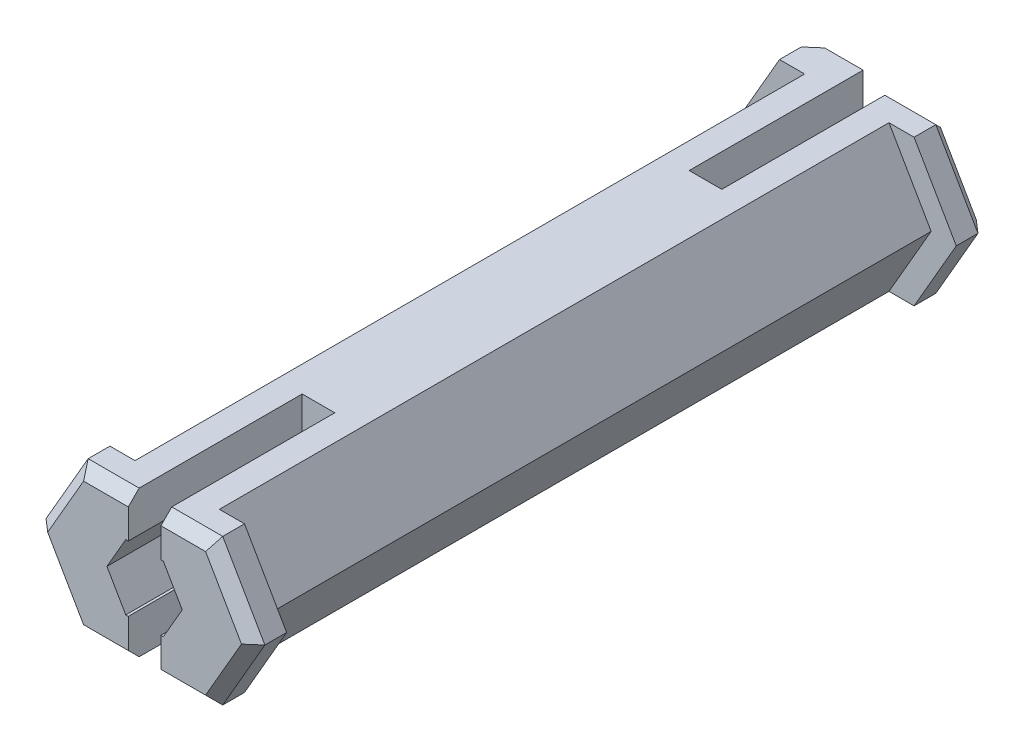
SolidWorks part; units mm, degrees
ref_plane "Plan de face" through (0, 0, 0) normal (1, 0, 0) x (0, 1, 0)
ref_plane "Plan de dessus" through (0, 0, 0) normal (0, 0, 1) x (0, 1, 0)
ref_plane "Plan de droite" through (0, 0, 0) normal (0, 1, 0) x (-1, 0, 0)
sketch "Esquisse1" plane through (0, 0, 0) normal (0, 0, 1) x (0, 1, 0)
  line L1 (0, 3.8798) -> (-3.36, 1.9399)
  line L2 (-3.36, 1.9399) -> (-3.36, -1.9399)
  line L3 (-3.36, -1.9399) -> (0, -3.8798)
  line L4 (0, -3.8798) -> (3.36, -1.9399)
  line L5 (3.36, -1.9399) -> (3.36, 1.9399)
  line L6 (3.36, 1.9399) -> (0, 3.8798)
  circle A0 centre (0, 0) radius 3.36 construction
  dimension "D1" = 6.72
extrude "Boss.-Extru.1" add sketch "Esquisse1" along normal mid plane 30.8
sketch "Esquisse2" plane through (0, 0, 15.4) normal (0, 0, 1) x (1, 0, 0)
  line L6 (-3.0946, 3.36) -> (3.0946, 3.36)
  line L7 (1.9399, 3.36) -> (-1.9399, 3.36) construction
  line L8 (-3.0946, -3.36) -> (3.0946, -3.36)
  line L9 (-1.9399, -3.36) -> (1.9399, -3.36) construction
  line L12 (-2.5172, 4.36) -> (-5.0345, 0)
  line L13 (-5.0345, 0) -> (-2.5172, -4.36)
  line L14 (-2.5172, -4.36) -> (2.5172, -4.36)
  line L15 (2.5172, -4.36) -> (5.0345, 0)
  line L16 (5.0345, 0) -> (2.5172, 4.36)
  line L17 (2.5172, 4.36) -> (-2.5172, 4.36)
  line L18 (-2.5172, 4.36) -> (-5.0345, 0)
  line L19 (-5.0345, 0) -> (-2.5172, -4.36)
  line L20 (-2.5172, -4.36) -> (2.5172, -4.36)
  line L21 (2.5172, -4.36) -> (5.0345, 0)
  line L22 (5.0345, 0) -> (2.5172, 4.36)
  line L23 (2.5172, 4.36) -> (-2.5172, 4.36)
  line M7 (-1.9399, 3.36) -> (-3.8798, 0)
  line M8 (-3.8798, 0) -> (-1.9399, -3.36)
  line M9 (-1.9399, -3.36) -> (1.9399, -3.36)
  line M10 (1.9399, -3.36) -> (3.8798, 0)
  line M11 (3.8798, 0) -> (1.9399, 3.36)
  line M12 (1.9399, 3.36) -> (-1.9399, 3.36)
  dimension "D1" = 1
extrude "Boss.-Extru.2" add sketch "Esquisse2" along normal blind 1.5 contours L18 L19 L8 L6 M8 M7 | L21 L22 L6 L8 M11 M10 | M12 M7 M8 M9 M10 M11
sketch "Esquisse4" plane through (0, 0, 16.9) normal (0, 0, 1) x (1, 0, 0)
  line L1 (-1.7321, 0) -> (-0.866, -1.5)
  line L2 (-0.866, -1.5) -> (0.866, -1.5)
  line L3 (0.866, -1.5) -> (1.7321, 0)
  line L4 (1.7321, 0) -> (0.866, 1.5)
  line L5 (0.866, 1.5) -> (-0.866, 1.5)
  line L6 (-0.866, 1.5) -> (-1.7321, 0)
  line L7 (-0.75, -4.2153) -> (0.75, -4.2153)
  line L8 (-0.75, -4.2153) -> (-0.75, 4.2153)
  line L9 (-0.75, 4.2153) -> (0.75, 4.2153)
  line L10 (0.75, -4.2153) -> (0.75, 4.2153)
  line L11 (-0.75, -4.2153) -> (0.75, 4.2153) construction
  line L12 (-0.75, 4.2153) -> (0.75, -4.2153) construction
  circle A0 centre (0, 0) radius 1.5 construction
  line M7 (-3.0946, -3.36) -> (3.0946, -3.36)
  line M10 (3.0946, 3.36) -> (-3.0946, 3.36)
  dimension "D1" = 3
  dimension "D2" = 1.5
extrude "Enlèv. mat.-Extru.1" cut sketch "Esquisse4" against normal blind 8 contours L10 L9 L8 M10 | L5 L10 L8 M10 | L2 L10 L5 L8 | L10 L2 L8 M7 | L10 L2 L3 L4 L5 | L2 L8 L5 L6 L1
mirror "Symétrie2" about plane through (0, 0, 0) normal (0, 0, 1) of "Boss.-Extru.2", "Enlèv. mat.-Extru.1"
chamfer "Chanfrein1" distance 0.5 angle 45 12 edges at (-1.9223, 3.36, 16.9) (-1.9223, -3.36, 16.9) (4.0645, -1.68, 16.9) (4.0645, 1.68, 16.9) (-4.0645, 1.68, 16.9) (-4.0645, -1.68, 16.9) (1.9223, -3.36, 16.9) (1.9223, 3.36, 16.9) (-4.0645, -1.68, -16.9) (-4.0645, 1.68, -16.9) (4.0645, 1.68, -16.9) (4.0645, -1.68, -16.9)
